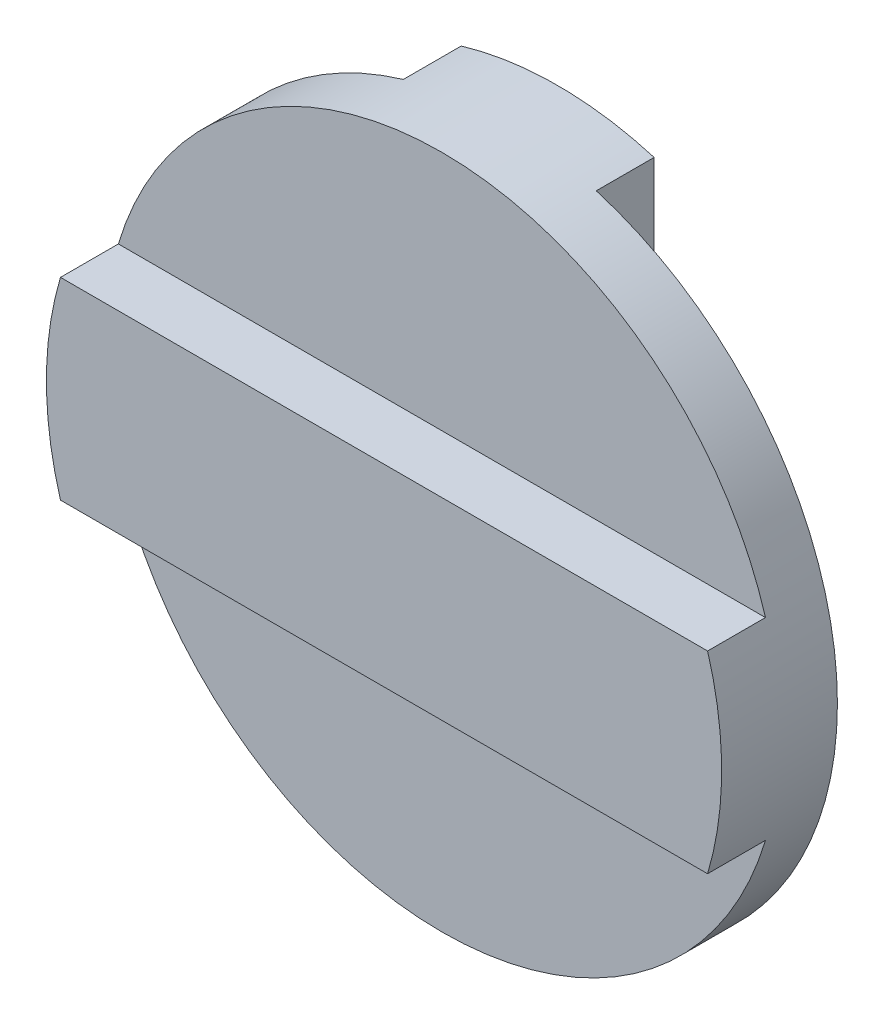
SolidWorks part; units mm, degrees
ref_plane "Front Plane" through (0, 0, 0) normal (0, 0, 1) x (1, 0, 0)
ref_plane "Top Plane" through (0, 0, 0) normal (0, 1, 0) x (1, 0, 0)
ref_plane "Right Plane" through (0, 0, 0) normal (1, 0, 0) x (0, 0, -1)
sketch "Sketch1" plane through (0, 0, 0) normal (0, 0, 1) x (1, 0, 0)
  line L0 (0, 57.2837) -> (0, -57.2837) construction
  line L1 (-80.5235, 0) -> (80.5235, 0) construction
  circle A0 centre (0, 0) radius 17.5
  point P4 (0, 0)
  point P7 (0, 0)
  dimension "D1" = 35
extrude "Boss-Extrude1" add sketch "Sketch1" along normal mid plane 3
sketch "Sketch2" plane through (0, 0, 1.5) normal (0, 0, 1) x (1, 0, 0)
  line L0 (-17.5, 0) -> (17.5, 0) construction
  line L1 (-16.7705, -5) -> (16.7705, -5)
  line L2 (-16.7705, 5) -> (16.7705, 5)
  line L3 (-17.5, 5) -> (17.5, 5) construction
  line L4 (-17.5, -5) -> (17.5, -5) construction
  circle A0 centre (0, 0) radius 17.5 construction
  arc A1 (-16.7705, 5) -> (-16.7705, -5) centre (0, 0) ccw
  arc A2 (16.7705, -5) -> (16.7705, 5) centre (0, 0) ccw
  dimension "D1" = 5
  dimension "D2" = 5
extrude "Boss-Extrude2" add sketch "Sketch2" along normal blind 3 contours L2 A2 L1 A1
sketch "Sketch3" plane through (0, 0, -1.5) normal (0, 0, -1) x (-1, 0, 0)
  line L0 (0, 17.5) -> (0, -17.5) construction
  line L1 (-5, 16.7705) -> (-5, -16.7705)
  line L2 (5, 16.7705) -> (5, -16.7705)
  line L3 (5, 17.5) -> (5, -17.5) construction
  line L4 (-5, 17.5) -> (-5, -17.5) construction
  circle A0 centre (0, 0) radius 17.5 construction
  arc A1 (5, 16.7705) -> (-5, 16.7705) centre (0, 0) ccw
  arc A2 (-5, -16.7705) -> (5, -16.7705) centre (0, 0) ccw
  point P15 (5, -2.6388)
  point P16 (0, -0.4636)
  dimension "D1" = 5
  dimension "D2" = 5
extrude "Boss-Extrude3" add sketch "Sketch3" along normal blind 3
